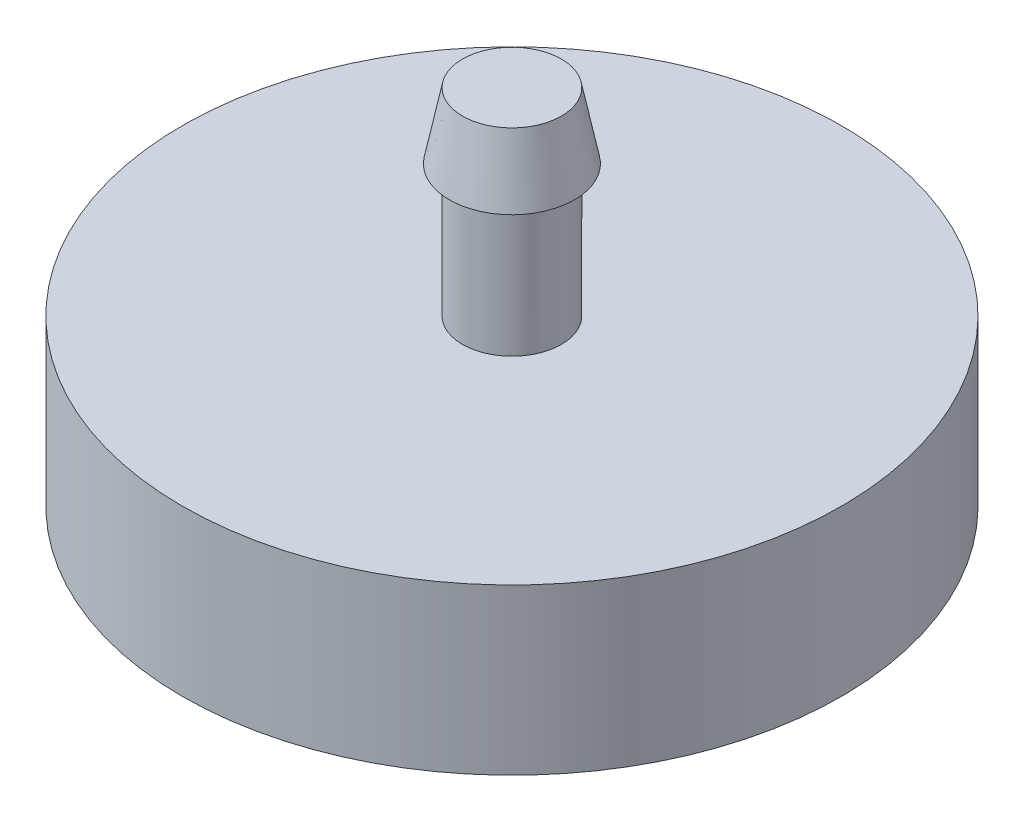
SolidWorks part; units mm, degrees
ref_plane "Front Plane" through (0, 0, 0) normal (0, 0, 1) x (1, 0, 0)
ref_plane "Top Plane" through (0, 0, 0) normal (0, 1, 0) x (1, 0, 0)
ref_plane "Right Plane" through (0, 0, 0) normal (1, 0, 0) x (0, 0, -1)
sketch "Sketch1" plane through (0, 0, 0) normal (0, 1, 0) x (1, 0, 0)
  circle A0 centre (0, 0) radius 5
  dimension "D1" = 10
extrude "Boss-Extrude1" add sketch "Sketch1" along normal blind 2.5
sketch "Sketch2" plane through (0, 2.5, 0) normal (0, 1, 0) x (1, 0, 0)
  circle A0 centre (0, 0) radius 0.75
  dimension "D1" = 1.5
extrude "Boss-Extrude2" add sketch "Sketch2" along normal blind 3
sketch "Sketch3" plane through (0, 0, 0) normal (0, 0, 1) x (1, 0, 0)
  line L0 (0.75, 5.5) -> (0.75, 4.5)
  line L1 (0.75, 2.5) -> (0.75, 5.5) construction
  line L2 (0.75, 4.5) -> (0.95, 4.5)
  line L3 (0.95, 4.5) -> (0.75, 5.5)
  line L4 (0, 0) -> (0, 5.5) construction
  line L5 (0.75, 5.5) -> (-0.75, 5.5) construction
  dimension "D1" = 0.2
  dimension "D2" = 1
revolve "Revolve1" add sketch "Sketch3" angle 360 about L4
